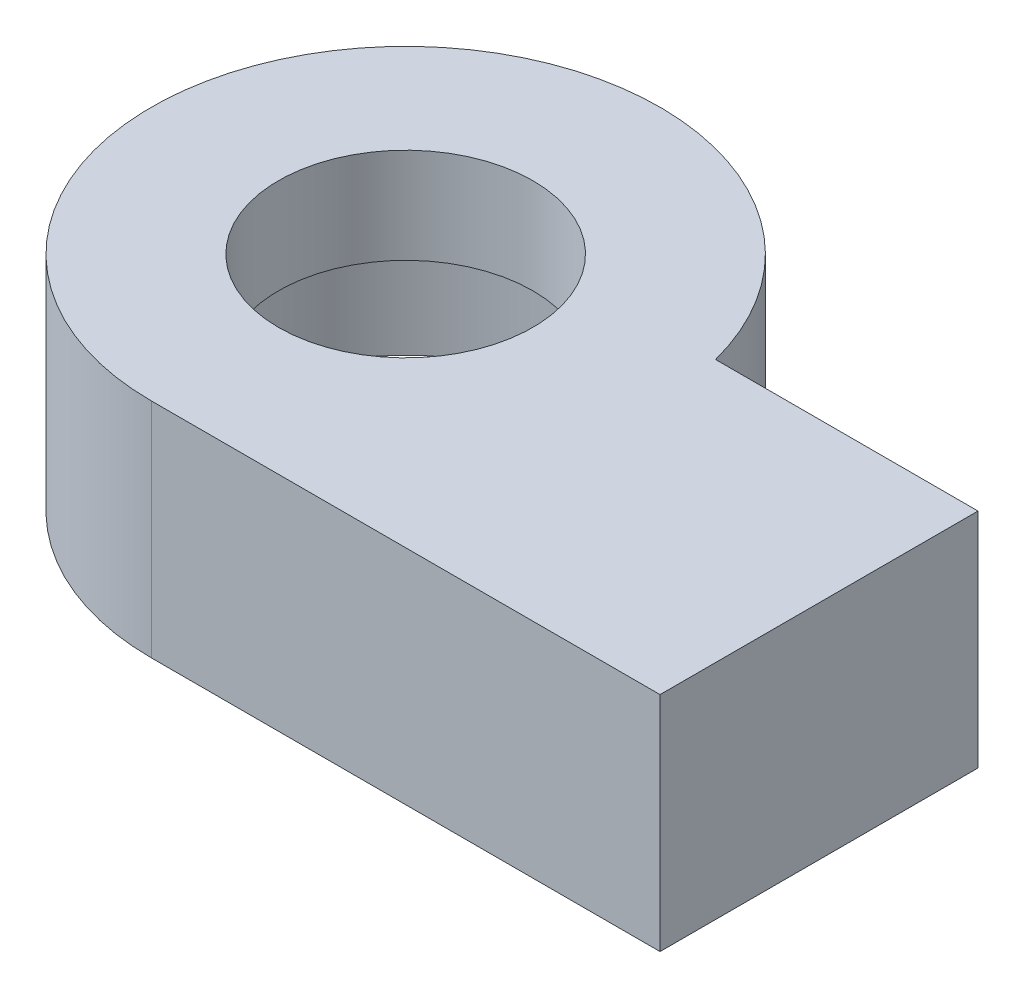
SolidWorks part; units mm, degrees
ref_plane "Front Plane" through (0, 0, 0) normal (0, 0, 1) x (1, 0, 0)
ref_plane "Top Plane" through (0, 0, 0) normal (0, 1, 0) x (1, 0, 0)
ref_plane "Right Plane" through (0, 0, 0) normal (1, 0, 0) x (0, 0, -1)
sketch "Sketch1" plane through (0, 0, 0) normal (0, 1, 0) x (1, 0, 0)
  line L0 (0, 0) -> (7.4493, 0) construction
  line L1 (0, -4) -> (8, -4)
  line L2 (3.873, 1) -> (8, 1)
  line L3 (8, 1) -> (8, -4)
  arc A0 (3.873, 1) -> (0, -4) centre (0, 0) ccw
  arc A1 (0, -4) -> (4, 0) centre (0, 0) ccw construction
  arc A2 (4, 0) -> (3.873, 1) centre (0, 0) ccw construction
  dimension "D1" = 8
  dimension "D2" = 8
  dimension "D3" = 1
extrude "Boss-Extrude1" add sketch "Sketch1" along normal blind 3.5
sketch "Sketch2" plane through (0, 0, 0) normal (0, -1, 0) x (1, 0, 0)
  circle A0 centre (0, 0) radius 3
  dimension "D1" = 6
extrude "Cut-Extrude1" cut sketch "Sketch2" against normal blind 2
sketch "Sketch3" plane through (0, 2, 0) normal (0, -1, 0) x (1, 0, 0)
  circle A0 centre (0, 0) radius 2
  dimension "D1" = 4
extrude "Cut-Extrude2" cut sketch "Sketch3" against normal through all
